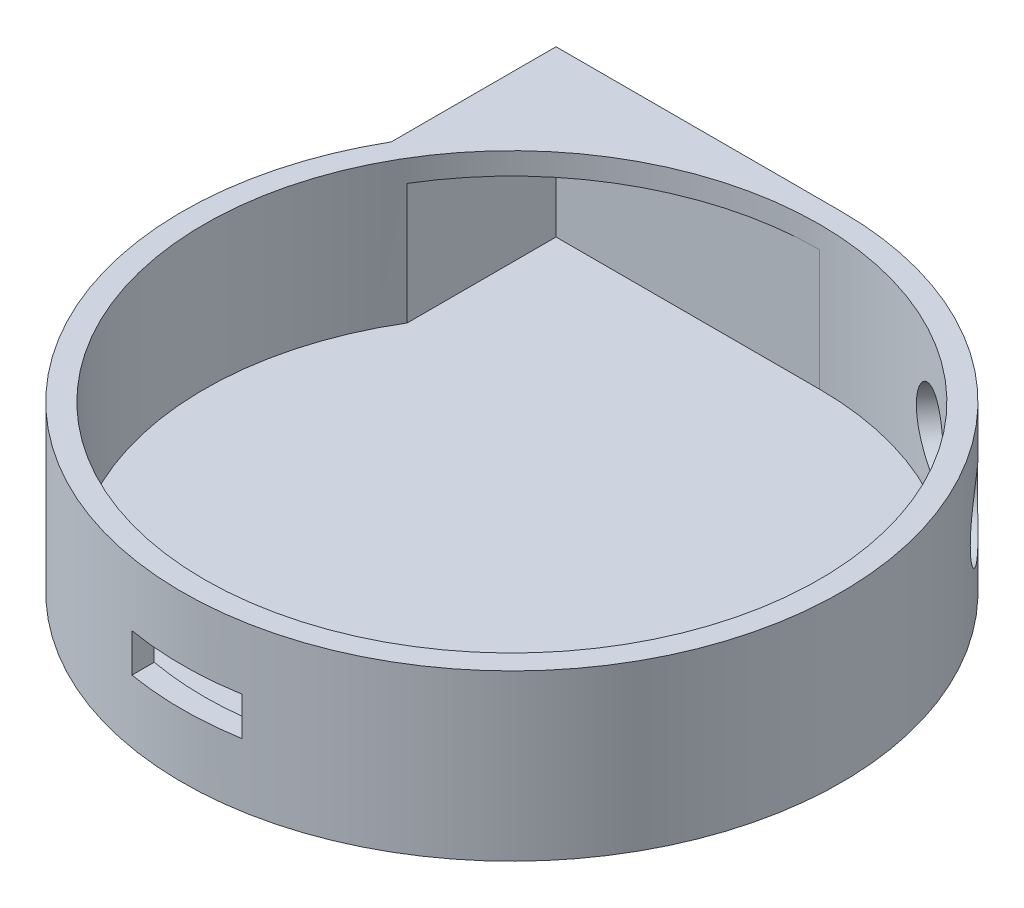
SolidWorks part; units mm, degrees
ref_plane "Front Plane" through (0, 0, 0) normal (0, 0, 1) x (1, 0, 0)
ref_plane "Top Plane" through (0, 0, 0) normal (0, 1, 0) x (1, 0, 0)
ref_plane "Right Plane" through (0, 0, 0) normal (1, 0, 0) x (0, 0, -1)
sketch "Sketch1" plane through (0, 0, 0) normal (0, 1, 0) x (1, 0, 0)
  line L0 (-25.9808, 15) -> (-25.9808, 30)
  line L1 (-25.9808, 30) -> (0, 30)
  arc A0 (-25.9808, 15) -> (0, 30) centre (0, 0) ccw
  dimension "D2" = 60
  dimension "D1" = 15
extrude "Boss-Extrude1" add sketch "Sketch1" along normal blind 2
sketch "Sketch2" plane through (0, 2, 0) normal (0, 1, 0) x (1, 0, 0)
  line L0 (0, 28) -> (-23.9808, 28)
  line L1 (-23.9808, 28) -> (-23.9808, 14.4542)
  line L2 (0, 30) -> (-25.9808, 30)
  line L3 (-25.9808, 30) -> (-25.9808, 15)
  line L4 (0, 30) -> (-25.9808, 30)
  line L5 (-25.9808, 30) -> (-25.9808, 15)
  arc A0 (-23.9808, 14.4542) -> (0, 28) centre (0, 0) ccw
  arc A1 (-25.9808, 15) -> (0, 30) centre (0, 0) ccw
  arc A2 (-25.9808, 15) -> (0, 30) centre (0, 0) ccw
  dimension "D1" = 0
  dimension "D2" = 2
extrude "Boss-Extrude2" add sketch "Sketch2" along normal blind 13
sketch "Sketch3" plane through (0, 15, 0) normal (0, 1, 0) x (1, 0, 0)
  line L4 (-23.9808, 14.4542) -> (-23.9808, 28)
  line L5 (-23.9808, 28) -> (-23.9808, 14.4542) construction
  line L6 (-23.9808, 28) -> (-23.9808, 14.4542) construction
  line L7 (-23.9808, 28) -> (0, 28)
  line L8 (0, 0) -> (0, 28) construction
  arc A1 (0, 28) -> (-23.9808, 14.4542) centre (0, 0) ccw
  arc A2 (-23.9808, 14.4542) -> (0, 28) centre (0, 0) ccw construction
  dimension "D1" = 28
extrude "Boss-Extrude3" add sketch "Sketch3" against normal blind 2
sketch "Sketch4" plane through (0, 0, 0) normal (0, -1, 0) x (1, 0, 0)
  circle A0 centre (0, 0) radius 12.5
  dimension "D1" = 25
extrude "Cut-Extrude2" cut sketch "Sketch4" against normal blind 1
ref_plane "USB_C_Port_Plane" through (0, 0, 30) normal (0, 0, 1) x (1, 0, 0)
sketch "Sketch5" plane through (0, 0, 30) normal (0, 0, 1) x (1, 0, 0)
  line L1 (-5, 9.25) -> (5, 9.25)
  line L2 (-5, 9.25) -> (-5, 5.75)
  line L3 (-5, 5.75) -> (5, 5.75)
  line L4 (5, 9.25) -> (5, 5.75)
  line L5 (-5, 9.25) -> (5, 5.75) construction
  line L6 (-5, 5.75) -> (5, 9.25) construction
  point P0 (0, 7.5)
  point P5 (0, 0)
  dimension "D1" = 3.5
  dimension "D2" = 10
  dimension "D3" = 7.5
extrude "USB_C_Cut" cut sketch "Sketch5" against normal blind 4
ref_plane "Volume_Buttons_Plane" through (19.2836, 0, -22.9813) normal (0.6428, 0, -0.766) x (0, -1, 0)
sketch "Sketch6" plane through (19.2836, 0, -22.9813) normal (0.6428, 0, -0.766) x (0, -1, 0)
  circle A0 centre (-7.5, 4.5) radius 3.5
  circle A1 centre (-7.5, -4.5) radius 3.5
  dimension "D3" = 7
  dimension "D1" = 7.5
  dimension "D2" = 4.5
  dimension "D4" = 9
extrude "Volume_Buttons_Cut" cut sketch "Sketch6" against normal blind 4
equation "\"wall_thickness\"= 2'mm"
equation "\"box_thickness\"= 15'mm"
equation "\"volume_button_radius\"= 7'mm"
equation "\"Volume_Buttons_Angle\"= 130'Degrees"
